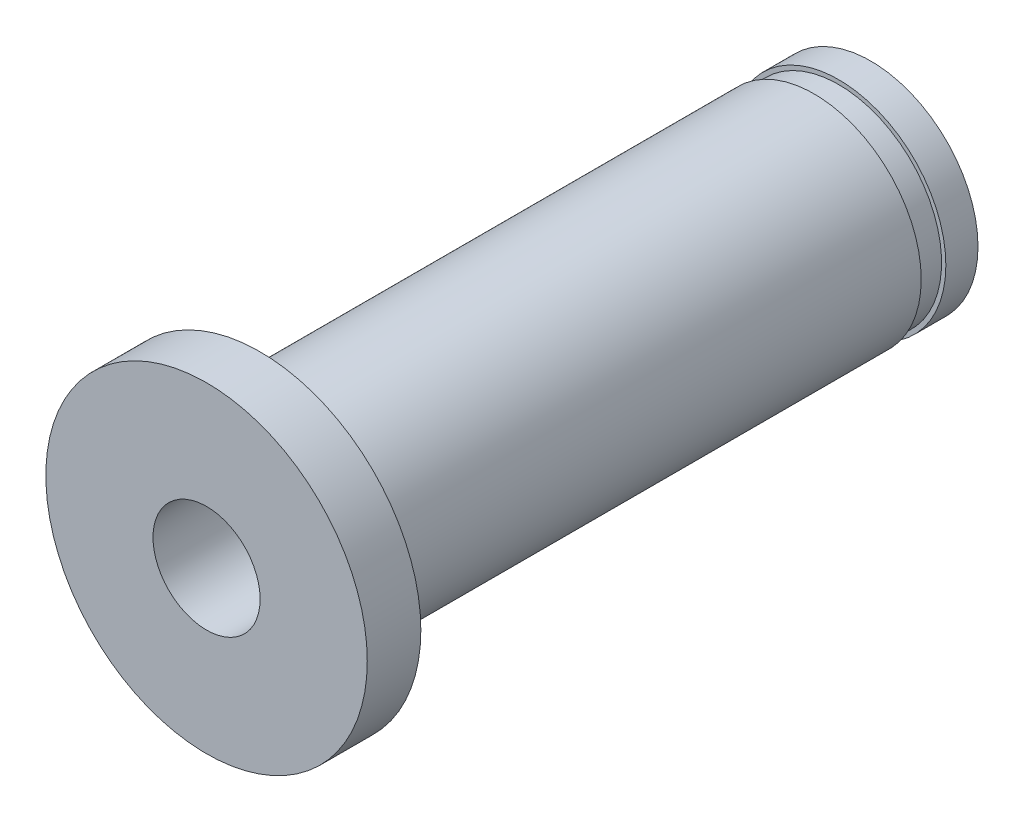
SolidWorks part; units mm, degrees
material "6061 Legierung"
ref_plane "Ebene vorne" through (0, 0, 0) normal (0, 0, 1) x (1, 0, 0)
ref_plane "Ebene oben" through (0, 0, 0) normal (0, 1, 0) x (1, 0, 0)
ref_plane "Ebene rechts" through (0, 0, 0) normal (1, 0, 0) x (0, 0, -1)
sketch "Skizze1" plane through (0, 0, 0) normal (0, 0, 1) x (1, 0, 0)
  circle A0 centre (0, 0) radius 5
  dimension "D1" = 10
extrude "Aufsatz-Linear austragen1" add sketch "Skizze1" along normal blind 31
hole_wizard "M6 Gewindebohrung1" positions "Skizze3" profile "Skizze5" tap size "M6" standard "ISO"
sketch "Skizze3" plane through (0, 0, 0) normal (0, 0, -1) x (-1, 0, 0)
  point P0 (0, 0)
  point P5 (0, 0)
sketch "Skizze5" plane through (0, 0, 0) normal (1, 0, 0) x (0, 1, 0)
  line L0 (0, 0) -> (0, 16.5022)
  line L1 (0, 16.5022) -> (2.5, 15)
  line L2 (2.5, 15) -> (2.5, 0)
  line L5 (2.5, 0) -> (0, 0)
  line L10 (0, 16.5022) -> (-2.5, 15) construction
  line L11 (0, -6.35) -> (0, 107.95) construction
  dimension "Bohrerdurchmesser" = 5
  dimension "Bohrungstiefe" = 15
  dimension "Spitzenwinkel" = 118
cosmetic thread "Bohrungsgewinde2" parameters "D1"=12, "D2"=6
hole_wizard "M6 Gewindebohrung2" positions "Skizze6" profile "Skizze7" tap size "M6" standard "ISO"
sketch "Skizze6" plane through (0, 0, 31) normal (0, 0, 1) x (1, 0, 0)
  point P0 (0, 0)
sketch "Skizze7" plane through (0, 0, 31) normal (1, 0, 0) x (0, -1, 0)
  line L0 (0, 0) -> (0, 16.5022)
  line L1 (0, 16.5022) -> (2.5, 15)
  line L2 (2.5, 15) -> (2.5, 0)
  line L5 (2.5, 0) -> (0, 0)
  line L10 (0, 16.5022) -> (-2.5, 15) construction
  line L11 (0, -6.35) -> (0, 107.95) construction
  dimension "Bohrerdurchmesser" = 5
  dimension "Bohrungstiefe" = 15
  dimension "Spitzenwinkel" = 118
cosmetic thread "Bohrungsgewinde3" parameters "D1"=12, "D2"=6
sketch "Skizze8" plane through (0, 0, 31) normal (0, 0, 1) x (1, 0, 0)
  circle A0 centre (0, 0) radius 7.5
  circle A1 centre (0, 0) radius 5
  dimension "D1" = 15
extrude "Aufsatz-Linear austragen3" add sketch "Skizze8" against normal blind 2.5
ref_plane "Ebene2" through (0, 0, 1.5) normal (0, 0, -1) x (-1, 0, 0)
sketch "Skizze9" plane through (0, 0, 1.5) normal (0, 0, -1) x (-1, 0, 0)
  circle A0 centre (0, 0) radius 4.8
  circle A1 centre (0, 0) radius 5.4046
  dimension "D1" = 9.6
extrude "Schnitt-Linear austragen1" cut sketch "Skizze9" against normal blind 1.15
